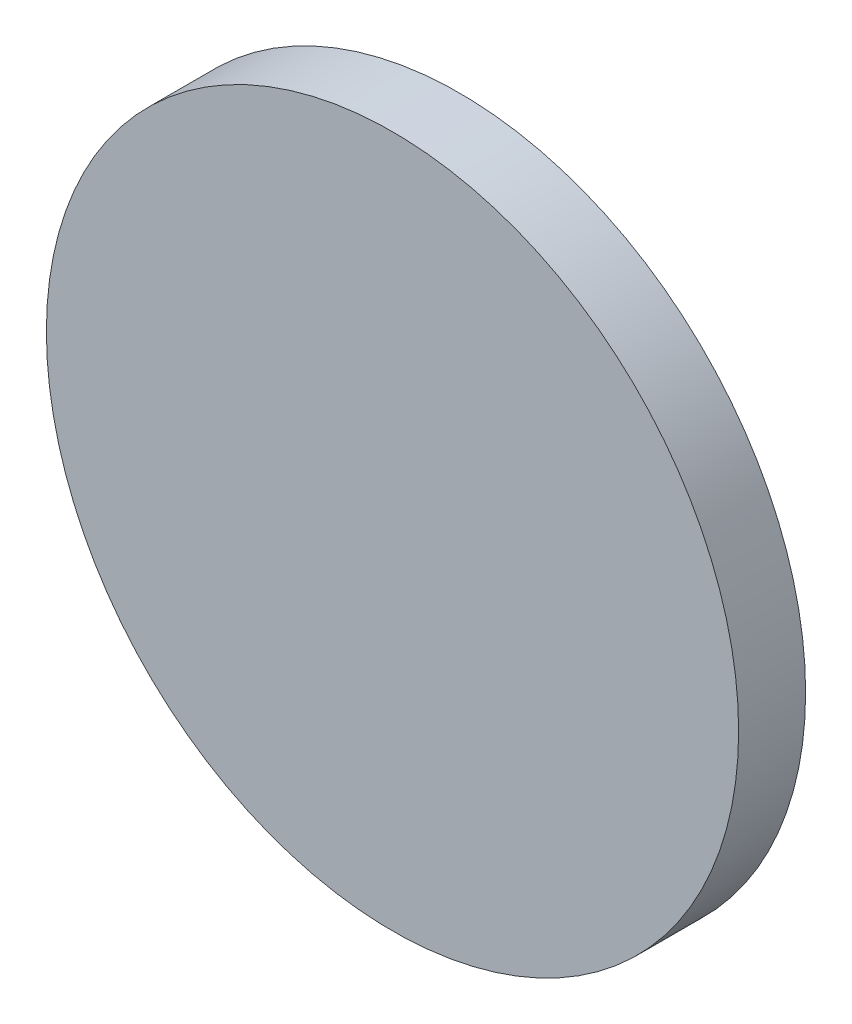
SolidWorks part; units mm, degrees
ref_plane "Front Plane" through (0, 0, 0) normal (0, 0, 1) x (1, 0, 0)
ref_plane "Top Plane" through (0, 0, 0) normal (0, 1, 0) x (1, 0, 0)
ref_plane "Right Plane" through (0, 0, 0) normal (1, 0, 0) x (0, 0, -1)
sketch "Sketch1" plane through (0, 0, 0) normal (0, 0, 1) x (1, 0, 0)
  circle A0 centre (0, 0) radius 16.4084
  dimension "D1" = 32.8168
extrude "Boss-Extrude1" add sketch "Sketch1" along normal blind 3.175
